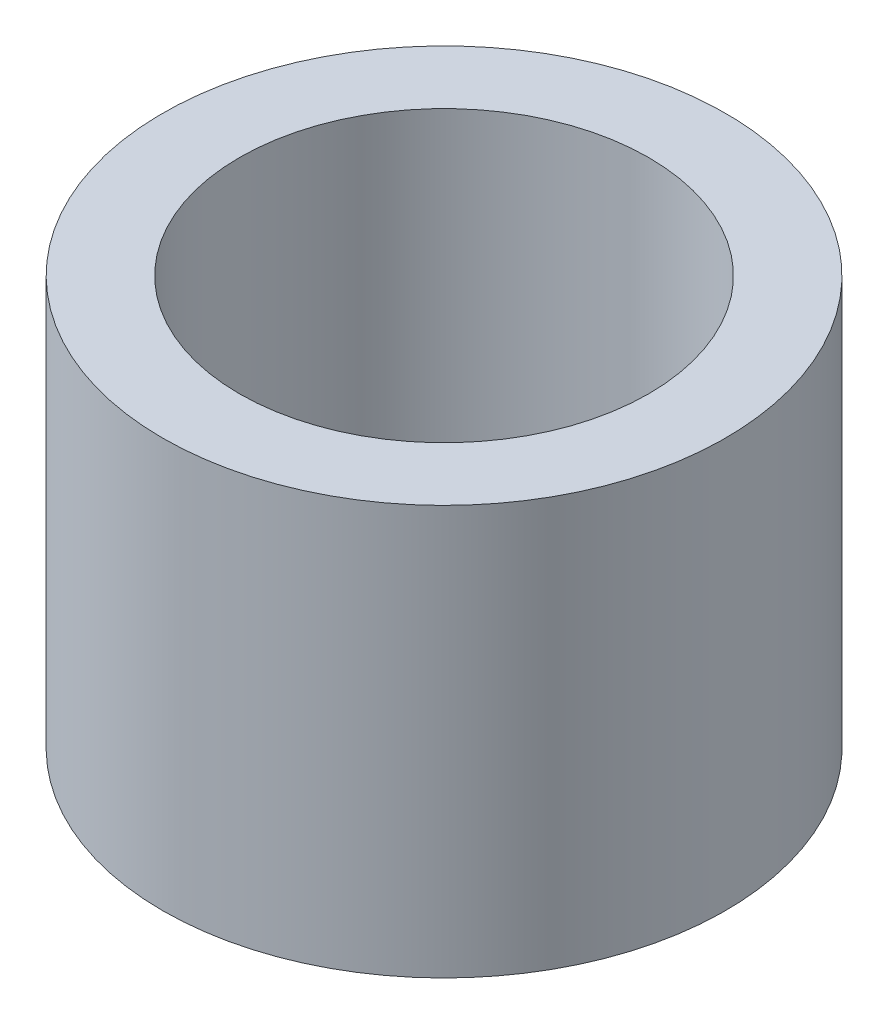
SolidWorks part; units mm, degrees
ref_plane "Front Plane" through (0, 0, 0) normal (0, 0, 1) x (1, 0, 0)
ref_plane "Top Plane" through (0, 0, 0) normal (0, 1, 0) x (1, 0, 0)
ref_plane "Right Plane" through (0, 0, 0) normal (1, 0, 0) x (0, 0, -1)
sketch "Sketch1" plane through (0, 0, 0) normal (0, 1, 0) x (1, 0, 0)
  circle A0 centre (0, 0) radius 8
  circle A1 centre (0, 0) radius 11
  dimension "D1" = 16
  dimension "D2" = 22
extrude "Boss-Extrude1" add sketch "Sketch1" along normal blind 16
